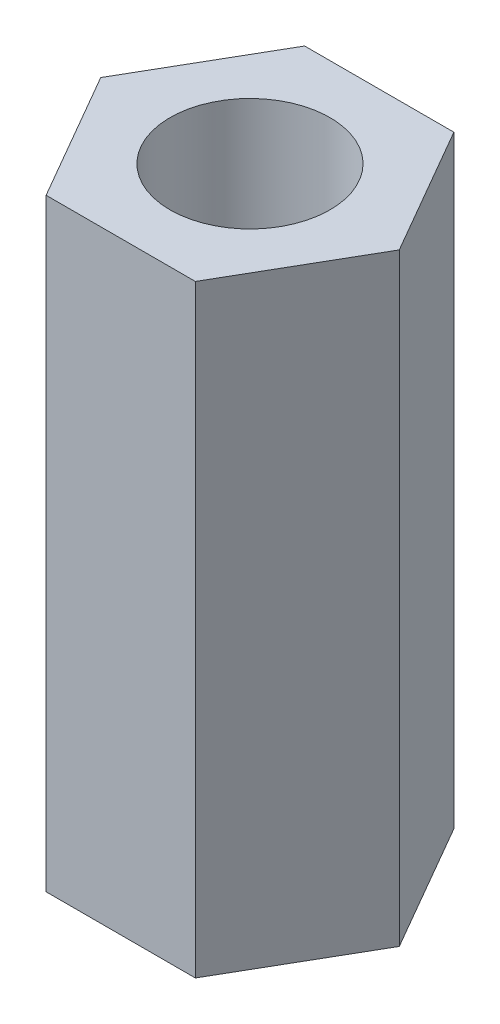
SolidWorks part; units mm, degrees
ref_plane "Front Plane" through (0, 0, 0) normal (0, 0, 1) x (1, 0, 0)
ref_plane "Top Plane" through (0, 0, 0) normal (0, 1, 0) x (1, 0, 0)
ref_plane "Right Plane" through (0, 0, 0) normal (1, 0, 0) x (0, 0, -1)
sketch "Sketch1" plane through (0, 0, 0) normal (0, 1, 0) x (1, 0, 0)
  line L1 (2.7496, 0) -> (1.3748, 2.3813)
  line L2 (1.3748, 2.3813) -> (-1.3748, 2.3813)
  line L3 (-1.3748, 2.3813) -> (-2.7496, 0)
  line L4 (-2.7496, 0) -> (-1.3748, -2.3813)
  line L5 (-1.3748, -2.3813) -> (1.3748, -2.3813)
  line L6 (1.3748, -2.3813) -> (2.7496, 0)
  circle A0 centre (0, 0) radius 2.3813 construction
  dimension "D1" = 4.7625
extrude "Boss-Extrude1" add sketch "Sketch1" along normal blind 11.1125
hole_wizard "#97 (0.0059) Diameter Hole1" positions "Sketch3" profile "Sketch2" hole size "#97" standard "ANSI Inch"
sketch "Sketch3" plane through (0, 11.1125, 0) normal (0, 1, 0) x (1, 0, 0)
  point P0 (0, 0)
sketch "Sketch2" plane through (0, 11.1125, 0) normal (1, 0, 0) x (0, 0, 1)
  line L0 (0, 0) -> (0, 26.2852)
  line L1 (0, 26.2852) -> (1.4732, 25.4)
  line L2 (1.4732, 25.4) -> (1.4732, 0)
  line L5 (1.4732, 0) -> (0, 0)
  line L10 (0, 26.2852) -> (-1.4732, 25.4) construction
  line L11 (0, -6.35) -> (0, 107.95) construction
  dimension "Hole Dia." = 2.9464
  dimension "Hole Depth" = 25.4
  dimension "Drill Angle" = 118
